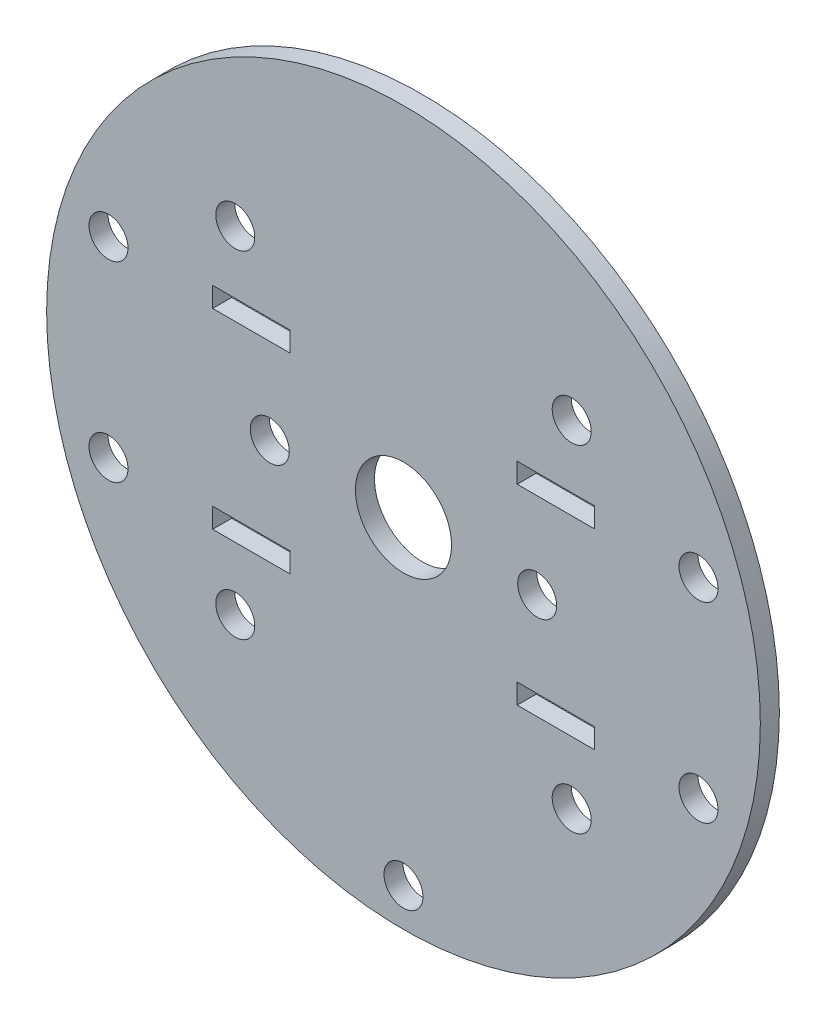
SolidWorks part; units mm, degrees
ref_plane "前视基准面" through (0, 0, 0) normal (0, 0, 1) x (1, 0, 0)
ref_plane "上视基准面" through (0, 0, 0) normal (0, 1, 0) x (1, 0, 0)
ref_plane "右视基准面" through (0, 0, 0) normal (1, 0, 0) x (0, 0, -1)
sketch "草图1" plane through (0, 0, 0) normal (0, 0, 1) x (1, 0, 0)
  line L0 (0, 0) -> (0, -37.5) construction
  line L1 (0, 0) -> (-28.479, -28.479) construction
  line L2 (3, -40.5) -> (-3, -40.5) construction
  line L3 (3, -40.5) -> (3, -34.5) construction
  line L4 (3, -34.5) -> (-3, -34.5) construction
  line L5 (-3, -40.5) -> (-3, -34.5) construction
  line L6 (3, -40.5) -> (-3, -34.5) construction
  line L7 (3, -34.5) -> (-3, -40.5) construction
  line L8 (20.05, -11.1) -> (20.05, -9)
  line L9 (11.95, -9) -> (20.05, -9)
  line L10 (11.95, -11.1) -> (11.95, -9)
  line L11 (11.95, -11.1) -> (20.05, -11.1)
  line L12 (0, 0) -> (37.5, 0) construction
  line L13 (11.95, 11.1) -> (11.95, 9)
  line L14 (20.05, 11.1) -> (20.05, 9)
  line L15 (11.95, 9) -> (20.05, 9)
  line L16 (11.95, 11.1) -> (20.05, 11.1)
  line L17 (-20.05, 11.1) -> (-20.05, 9)
  line L18 (-11.95, 11.1) -> (-11.95, 9)
  line L19 (-11.95, 9) -> (-20.05, 9)
  line L20 (-11.95, 11.1) -> (-20.05, 11.1)
  line L21 (-11.95, -11.1) -> (-11.95, -9)
  line L22 (-20.05, -11.1) -> (-20.05, -9)
  line L23 (-11.95, -9) -> (-20.05, -9)
  line L24 (-11.95, -11.1) -> (-20.05, -11.1)
  line L25 (-11.95, -9) -> (-20.05, -11.1) construction
  line L26 (-16, -10.05) -> (-31, -10.05) construction
  circle A0 centre (0, 0) radius 37.5
  circle A1 centre (0, 0) radius 5.05
  circle A2 centre (-3, -34.5) radius 1.55 construction
  circle A3 centre (3, -34.5) radius 1.55 construction
  circle A4 centre (0, 0) radius 25 construction
  circle A5 centre (-17.6777, -17.6777) radius 2.05
  circle A6 centre (-17.6777, 17.6777) radius 2.05
  circle A7 centre (17.6777, 17.6777) radius 2.05
  circle A8 centre (17.6777, -17.6777) radius 2.05
  circle A10 centre (-31, -10.05) radius 2.05
  circle A11 centre (-31, 10.05) radius 2.05
  circle A12 centre (31, 10.05) radius 2.05
  circle A13 centre (31, -10.05) radius 2.05
  circle A14 centre (0, 0) radius 14.05 construction
  circle A15 centre (14.05, 0) radius 2.05
  circle A16 centre (-14.05, 0) radius 2.05
  circle A18 centre (0, -33.5) radius 2.05
  dimension "D1" = 75
  dimension "D2" = 10.1
  dimension "D5" = 50
  dimension "D7" = 4
  dimension "D8" = 18
  dimension "D9" = 4
  dimension "D3" = 6
  dimension "D4" = 6
  dimension "D6" = 45
extrude "凸台-拉伸1" add sketch "草图1" along normal blind 2
